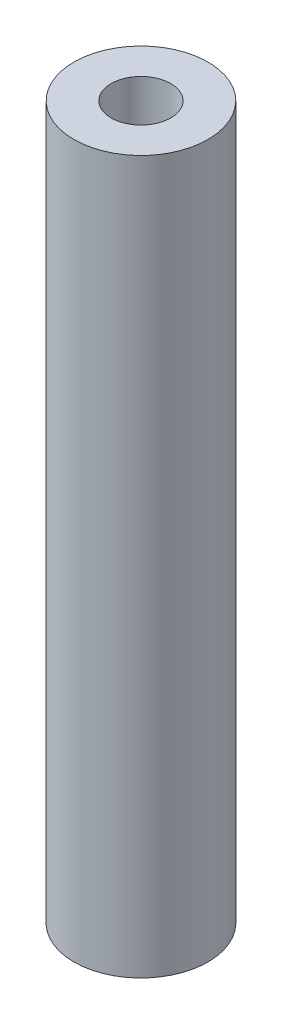
SolidWorks part; units mm, degrees
ref_plane "Front Plane" through (0, 0, 0) normal (0, 0, 1) x (1, 0, 0)
ref_plane "Top Plane" through (0, 0, 0) normal (0, 1, 0) x (1, 0, 0)
ref_plane "Right Plane" through (0, 0, 0) normal (1, 0, 0) x (0, 0, -1)
sketch "Sketch1" plane through (0, 0, 0) normal (0, 1, 0) x (1, 0, 0)
  circle A0 centre (0, 0) radius 1.2
  circle A1 centre (0, 0) radius 2.7
  dimension "D1" = 2.4
  dimension "D2" = 1.5
extrude "Boss-Extrude1" add sketch "Sketch1" along normal blind 28.68
